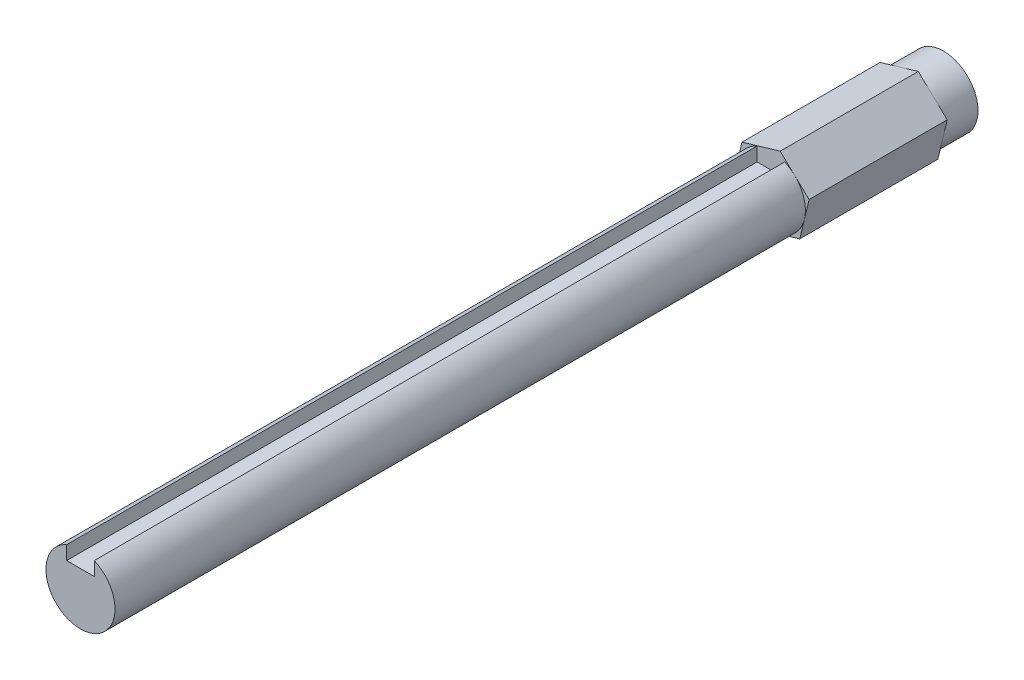
SolidWorks part; units mm, degrees
ref_plane "前视基准面" through (0, 0, 0) normal (0, 0, 1) x (1, 0, 0)
ref_plane "上视基准面" through (0, 0, 0) normal (0, 1, 0) x (1, 0, 0)
ref_plane "右视基准面" through (0, 0, 0) normal (1, 0, 0) x (0, 0, -1)
sketch "草图1" plane through (0, 0, 0) normal (0, 0, 1) x (1, 0, 0)
  line L1 (5.5362, 1.6383) -> (1.3493, 5.6136)
  line L2 (1.3493, 5.6136) -> (-4.1869, 3.9754)
  line L3 (-4.1869, 3.9754) -> (-5.5362, -1.6383)
  line L4 (-5.5362, -1.6383) -> (-1.3493, -5.6136)
  line L5 (-1.3493, -5.6136) -> (4.1869, -3.9754)
  line L6 (4.1869, -3.9754) -> (5.5362, 1.6383)
  circle A0 centre (0, 0) radius 5 construction
extrude "凸台-拉伸1" add sketch "草图1" along normal blind 20
sketch "草图2" plane through (0, 0, 0) normal (0, 0, -1) x (-1, 0, 0)
  circle A0 centre (0, 0) radius 5
extrude "凸台-拉伸2" add sketch "草图2" along normal blind 5
sketch "草图7" plane through (0, 0, 20) normal (0, 0, 1) x (1, 0, 0)
  circle A0 centre (0, 0) radius 5
extrude "凸台-拉伸4" add sketch "草图7" along normal blind 100
sketch "草图8" plane through (0, 0, 120) normal (0, 0, 1) x (1, 0, 0)
  line L0 (-2, 2.5826) -> (-2, 5.5826)
  line L1 (2, 2.5826) -> (2, 5.5826)
  line L2 (2, 5.5826) -> (-2, 5.5826)
  line L5 (2, 2.5826) -> (-2, 2.5826)
extrude "切除-拉伸1" cut sketch "草图8" against normal blind 100
